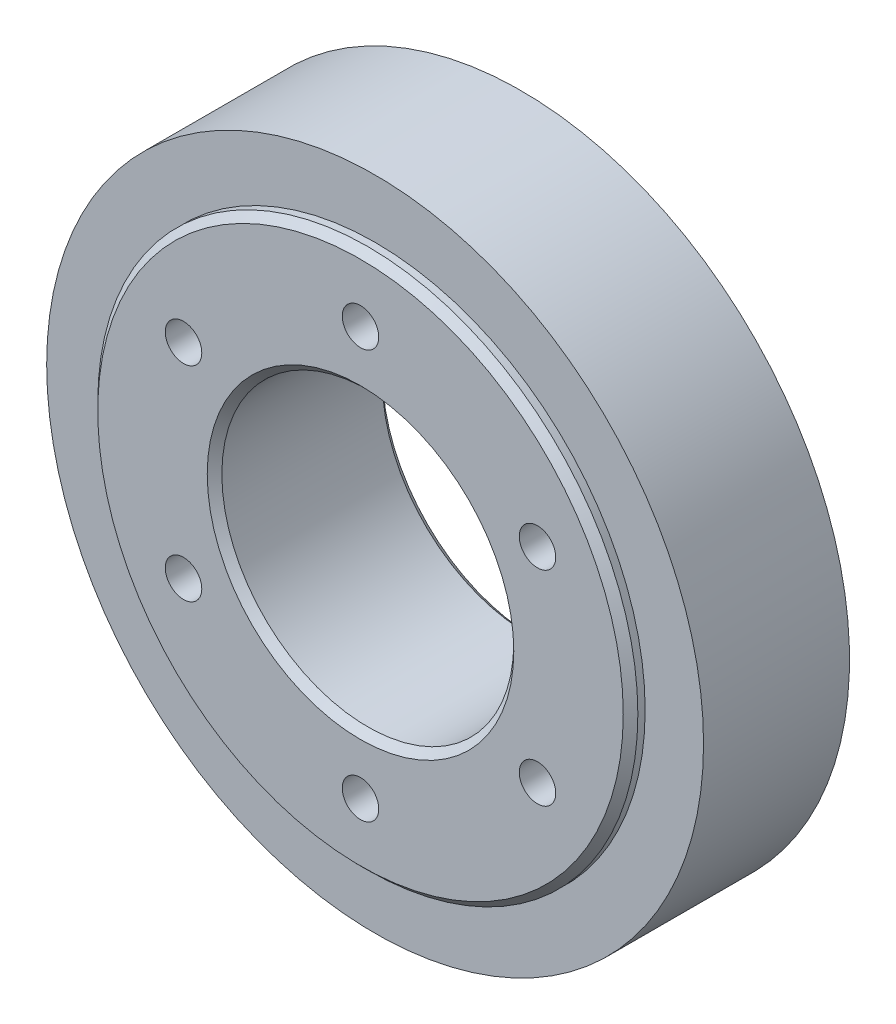
SolidWorks part; units mm, degrees
material "AISI 304"
ref_plane "정면" through (0, 0, 0) normal (0, 0, 1) x (1, 0, 0)
ref_plane "윗면" through (0, 0, 0) normal (0, 1, 0) x (1, 0, 0)
ref_plane "우측면" through (0, 0, 0) normal (1, 0, 0) x (0, 0, -1)
sketch "스케치1" plane through (0, 0, 0) normal (0, 0, 1) x (1, 0, 0)
  circle A0 centre (0, 0) radius 10
  circle A1 centre (0, 0) radius 22.5
  dimension "D1" = 20
  dimension "D2" = 45
extrude "보스-돌출1" add sketch "스케치1" along normal mid plane 12
sketch "Sketch1" plane through (0, 0, -6) normal (0, 0, -1) x (-1, 0, 0)
  circle A0 centre (0, 0) radius 18.5
  dimension "D1" = 37
extrude "Cut-Extrude1" cut sketch "Sketch1" against normal blind 1 flip side to cut
mirror "Mirror1" about plane through (0, 0, 0) normal (0, 0, 1) of "Cut-Extrude1"
hole_wizard "M3 Tapped Hole1" positions "스케치3" profile "스케치2" tap size "M3" standard "ISO" end condition through all
sketch "스케치3" plane through (0, 0, 6) normal (0, 0, 1) x (1, 0, 0)
  point P0 (0, 14)
  dimension "D1" = 14
sketch "스케치2" plane through (0, 14, 6) normal (1, 0, 0) x (0, -1, 0)
  line L0 (0, 0) -> (0, 12)
  line L1 (0, 12) -> (1.25, 12)
  line L2 (1.25, 12) -> (1.25, 0)
  line L5 (1.25, 0) -> (0, 0)
  line L11 (0, -6.35) -> (0, 107.95) construction
  dimension "°üÅë ÅÇ µå¸± Áö¸§" = 2.5
  dimension "°üÅë ÅÇ µå¸± ±íÀÌ" = 12
cosmetic thread "구멍 나사산1" parameters "D2"=3
pattern_circular "원형 패턴1" count 6 over 360 about axis through (0, 0, 0) along (0, 0, 1) of "M3 Tapped Hole1"
chamfer "모따기1" distance 0.5 angle 45 4 edges at (10, 0, -6) (10, 0, 6) (-18.5, 0, 6) (-18.5, 0, -6)
